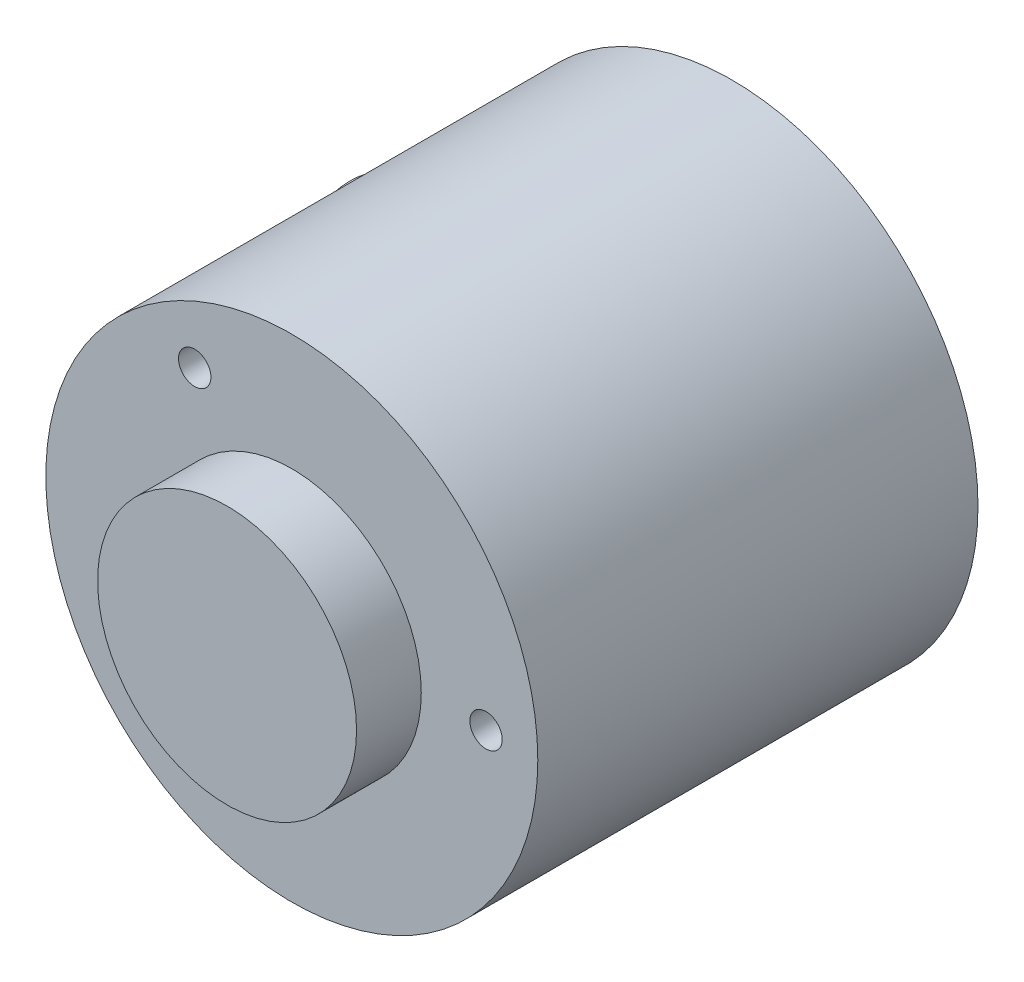
SolidWorks part; units mm, degrees
ref_plane "前视基准面" through (0, 0, 0) normal (0, 0, 1) x (1, 0, 0)
ref_plane "上视基准面" through (0, 0, 0) normal (0, 1, 0) x (1, 0, 0)
ref_plane "右视基准面" through (0, 0, 0) normal (1, 0, 0) x (0, 0, -1)
other "Configuration Table"
ref_plane "Plane_z_-34_0" through (0, 0, -34) normal (0, 0, 1) x (1, 0, 0)
sketch "草图1" plane through (0, 0, -34) normal (0, 0, 1) x (1, 0, 0)
  circle A0 centre (0, 0) radius 19
extrude "Housing_OD38_L34_from_drawing" add sketch "草图1" along normal blind 34
sketch "草图2" plane through (0, 0, 0) normal (0, 0, 1) x (1, 0, 0)
  circle A0 centre (0, 0) radius 10
extrude "Pilot_OD20_L5" add sketch "草图2" along normal blind 5
ref_plane "Plane_x_-22_2" through (-22, 0, 0) normal (1, 0, 0) x (0, 0, -1)
sketch "草图3" plane through (-22, 0, 0) normal (1, 0, 0) x (0, 0, -1)
  circle A0 centre (26.5, 0) radius 5
extrude "Side_cable_gland_ENVELOPE_EST" add sketch "草图3" along normal blind 5
sketch "草图4" plane through (0, 0, 0) normal (0, 0, 1) x (1, 0, 0)
  circle A0 centre (15, 0) radius 1.25
  circle A1 centre (-7.5, 12.9904) radius 1.25
  circle A2 centre (-7.5, -12.9904) radius 1.25
extrude "Front_3xM3_PCD30_depth6_reference" cut sketch "草图4" against normal blind 6
